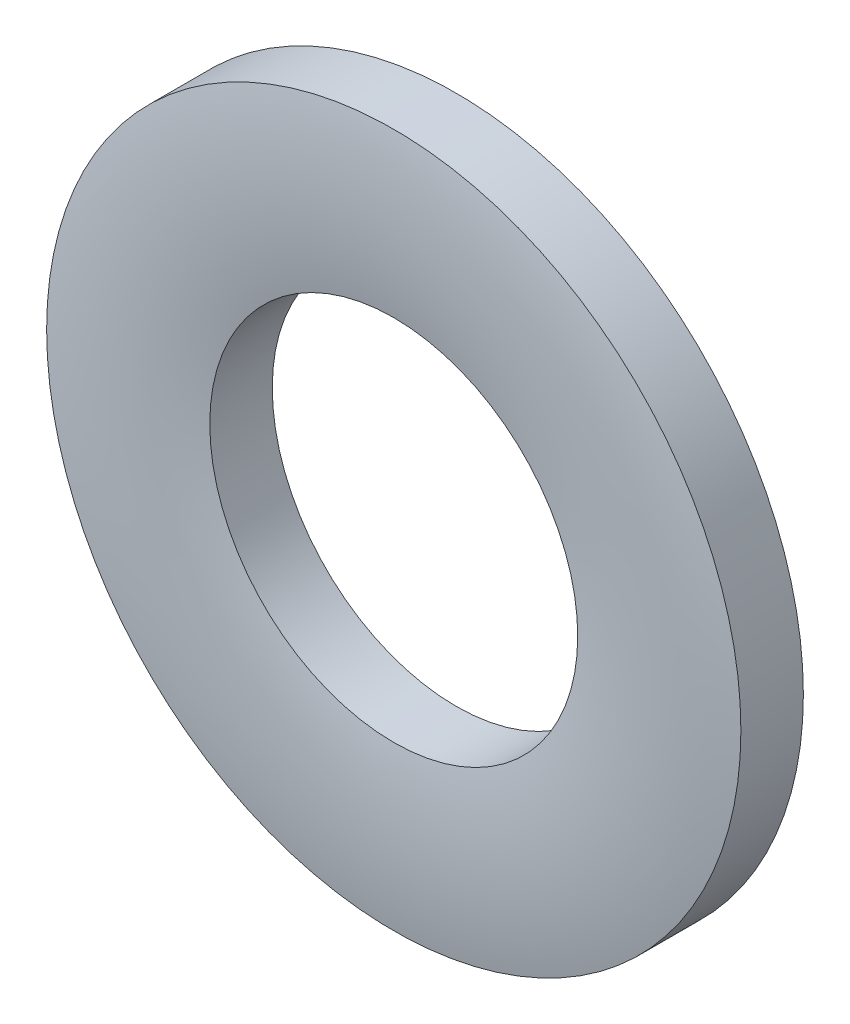
SolidWorks part; units mm, degrees
ref_plane "Front Plane" through (0, 0, 0) normal (0, 0, 1) x (1, 0, 0)
ref_plane "Top Plane" through (0, 0, 0) normal (0, 1, 0) x (1, 0, 0)
ref_plane "Right Plane" through (0, 0, 0) normal (1, 0, 0) x (0, 0, -1)
sketch "Sketch1" plane through (0, 0, 0) normal (0, 0, 1) x (1, 0, 0)
  circle A0 centre (0, 0) radius 2.65
  circle A1 centre (0, 0) radius 5
  dimension "ID" = 5.3
  dimension "OD" = 10
sketch "Sketch2" plane through (0, 0, 0) normal (1, 0, 0) x (0, 0, -1)
  line L0 (-0.5, 5) -> (0.5, 5) construction
  line L1 (-0.5, 0) -> (0.5, 0) construction
  point P2 (0, 5)
  dimension "Thickness Range" = 1
sketch "Sketch3" plane through (0, 0, 0) normal (1, 0, 0) x (0, 0, -1)
  line L0 (0.5, 5) -> (-0.4, 5)
  line L1 (0.5, 2.65) -> (-0.4, 2.65)
  line L2 (0.5, 2.65) -> (0.5, 5)
  line L3 (-0.5, 5) -> (-0.5, 2.65) construction
  arc A0 (-0.4, 2.65) -> (-0.4, 5) centre (6.4531, 3.825) cw
  point P9 (0, 2.65)
  dimension "D1" = 0.1
revolve "Revolve1" add sketch "Sketch3" angle 360 about L1
equation "\"D1@Sketch3\"=\"Thickness Range@Sketch2\"*.1"
